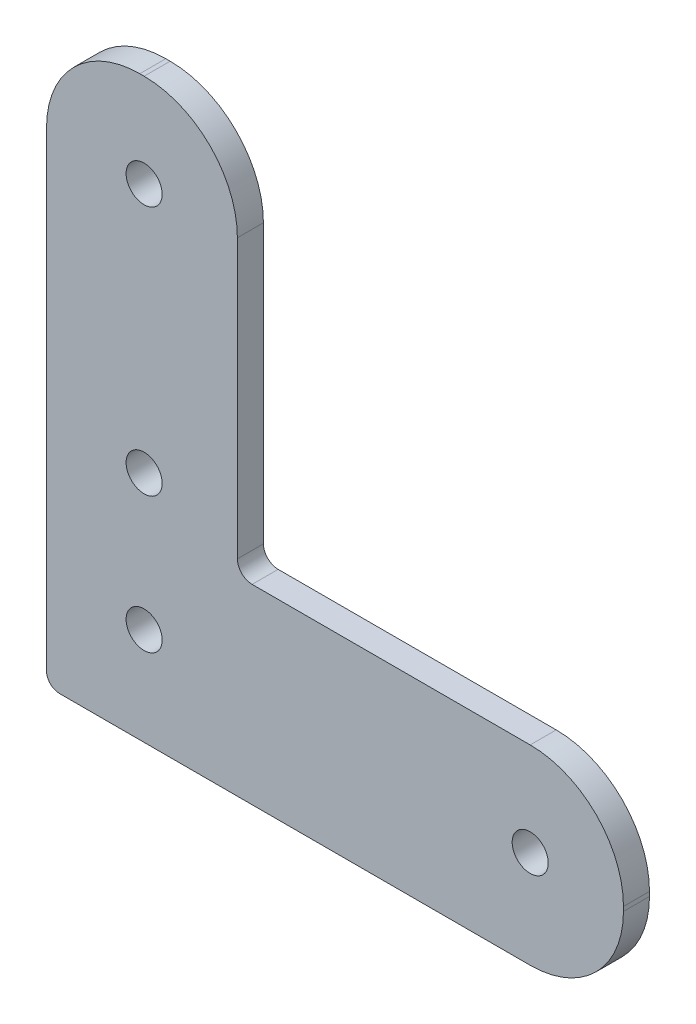
SolidWorks part; units mm, degrees
material "PET"
ref_plane "Front Plane" through (0, 0, 0) normal (0, 0, 1) x (1, 0, 0)
ref_plane "Top Plane" through (0, 0, 0) normal (0, 1, 0) x (1, 0, 0)
ref_plane "Right Plane" through (0, 0, 0) normal (1, 0, 0) x (0, 0, -1)
sketch "Sketch1" plane through (0, 0, 0) normal (0, 0, 1) x (1, 0, 0)
  line L0 (0, 0) -> (0, 133)
  line L1 (22.5, 22.5) -> (67, 22.5) construction
  line L2 (67, 22.5) -> (111.5, 22.5) construction
  line L3 (22.5, 22.5) -> (22.5, 53.7884) construction
  line L4 (45, 133) -> (0, 133)
  line L5 (133, 0) -> (0, 0)
  line L6 (22.5, 53.7884) -> (22.5, 85.0768) construction
  line L7 (133, 45) -> (133, 0)
  line L9 (133, 22.5) -> (111.5, 22.5) construction
  line L10 (22.5, 133) -> (22.5, 85.0768) construction
  line L11 (44, 133) -> (44, 44)
  line L12 (44, 44) -> (133, 44)
  circle A0 centre (22.5, 22.5) radius 4.1188 construction
  circle A1 centre (22.5, 111.5) radius 4.1187 construction
  circle A2 centre (111.5, 22.5) radius 4.1188 construction
  circle A3 centre (22.5, 53.7884) radius 4.1188 construction
  dimension "D1" = 21.5
  dimension "D2" = 22.5
  dimension "D7" = 8.2375
  dimension "D8" = 8.2375
  dimension "C" = 133
  dimension "D3" = 31.2884
  dimension "B" = 133
  dimension "D4" = 22.5
  dimension "D5" = 21.5
  dimension "D6" = 21.5
extrude "Boss-Extrude1" add sketch "Sketch1" along normal mid plane 6 contours L12 L11 L4 L0 L5 L7 A3 A2 A1 A0
fillet "Fillet4" radius 21.5 4 edges at (133, 44, 0) (133, 0, 0) (44, 133, 0) (0, 133, 0)
fillet "Fillet5" radius 3.4 1 edges at (44, 44, 0)
fillet "Fillet6" radius 3 1 edges at (0, 0, 0)
hole_wizard "5/16 Clearance Hole1" positions "Sketch4" profile "Sketch3" hole size "5/16" standard "ANSI Inch" end condition through all
sketch "Sketch4" plane through (0, 0, 3) normal (0, 0, 1) x (1, 0, 0)
  point P0 (22.5, 111.5)
  point P3 (22.5, 53.7884)
  point P6 (22.5, 22.5)
  point P9 (111.5, 22.5)
sketch "Sketch3" plane through (22.5, 111.5, 3) normal (1, 0, 0) x (0, -1, 0)
  line L0 (0, 0) -> (0, 6)
  line L1 (0, 6) -> (4.1592, 6)
  line L2 (4.1592, 6) -> (4.1592, 0)
  line L5 (4.1592, 0) -> (0, 0)
  line L11 (0, -6.35) -> (0, 107.95) construction
  dimension "Thru Hole Dia." = 8.3185
  dimension "Thru Hole Depth" = 6
